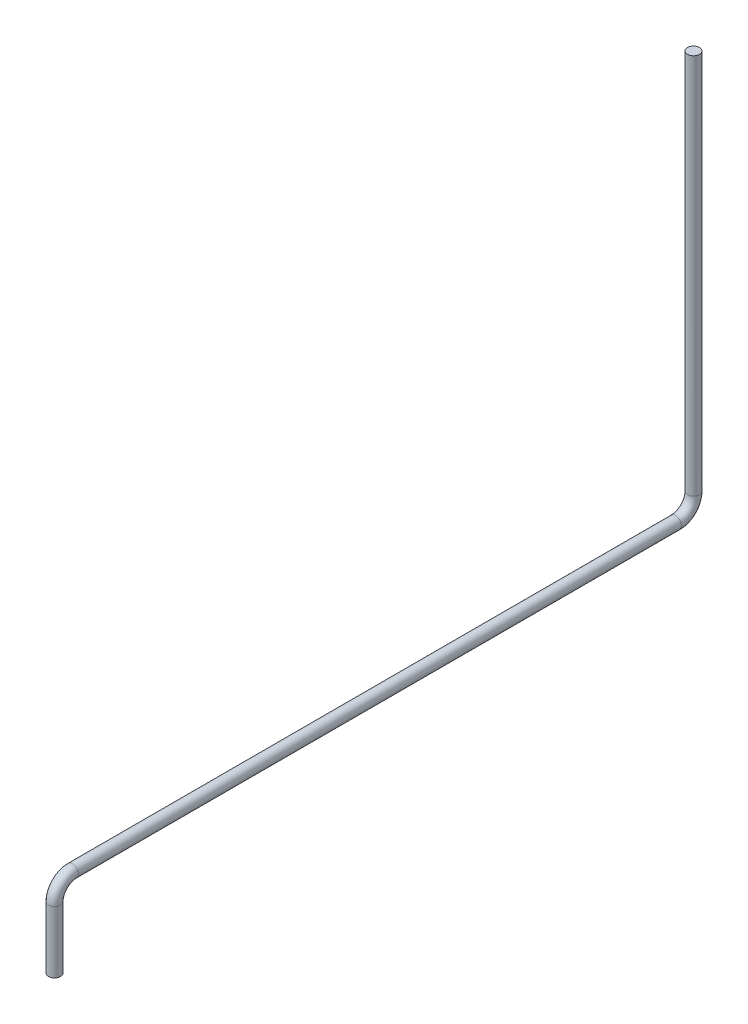
SolidWorks part; units mm, degrees
ref_plane "Alzado" through (0, 0, 0) normal (0, 0, 1) x (1, 0, 0)
ref_plane "Planta" through (0, 0, 0) normal (0, 1, 0) x (1, 0, 0)
ref_plane "Vista lateral" through (0, 0, 0) normal (1, 0, 0) x (0, 0, -1)
sketch "Croquis1" plane through (0, 0, 0) normal (0, 1, 0) x (1, 0, 0)
  circle A0 centre (0, 0) radius 15
  dimension "D1" = 30
extrude "Saliente-Extruir1" add sketch "Croquis1" against normal blind 100
sketch3d "Croquis3D1"
  line L0 (0, -100, 0) -> (0, -955, 0)
  line L1 (0, -100, 0) -> (0, 0, 0) construction
  line L2 (0, -1000, 45) -> (0, -1000, 1555)
  line L3 (0, -1045, 1600) -> (0, -1200, 1600)
  arc A0 (0, -1000, 1555) -> (0, -1045, 1600) centre (0, -1045, 1555) ccw
  arc A1 (0, -955, 0) -> (0, -1000, 45) centre (0, -955, 45) ccw
  point P8 (0, -1000, 1600)
  point P9 (45, -1045, 1555)
  point P12 (0, -1000, 0)
  point P13 (-45, -955, 45)
  dimension "D4" = 45
  dimension "D1" = 900
  dimension "D2" = 1600
  dimension "D3" = 200
sketch "Croquis2" plane through (0, -100, 0) normal (0, -1, 0) x (1, 0, 0)
  circle A0 centre (0, 0) radius 15
sweep "Barrer1" add profiles "Croquis2" path "Croquis3D1"
